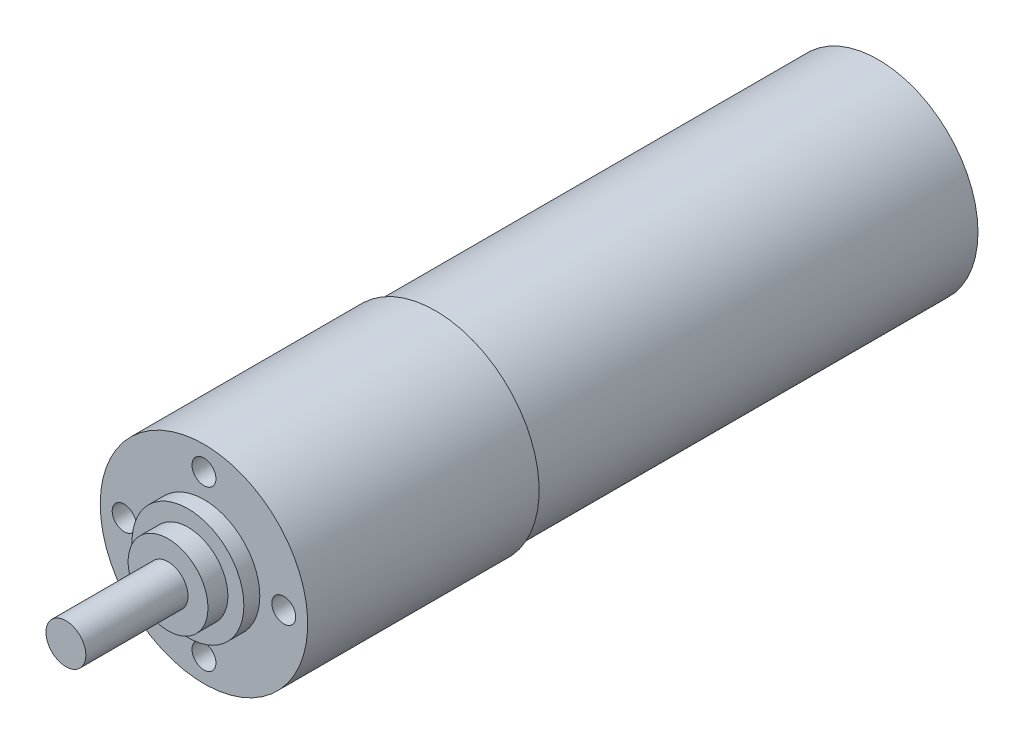
SolidWorks part; units mm, degrees
ref_plane "정면" through (0, 0, 0) normal (0, 0, 1) x (1, 0, 0)
ref_plane "윗면" through (0, 0, 0) normal (0, 1, 0) x (1, 0, 0)
ref_plane "우측면" through (0, 0, 0) normal (1, 0, 0) x (0, 0, -1)
sketch "스케치1" plane through (0, 0, 0) normal (0, 0, 1) x (1, 0, 0)
  circle A0 centre (0, 0) radius 12.5
  dimension "D1" = 25
extrude "돌출1" add sketch "스케치1" along normal blind 55.5
sketch "스케치2" plane through (0, 0, 55.5) normal (0, 0, 1) x (1, 0, 0)
  circle A0 centre (0, 0) radius 13
extrude "보스-돌출1" add sketch "스케치2" along normal blind 29
sketch "스케치3" plane through (0, 0, 84.5) normal (0, 0, 1) x (1, 0, 0)
  circle A0 centre (0, 0) radius 7
extrude "보스-돌출2" add sketch "스케치3" along normal blind 2
sketch "스케치4" plane through (0, 0, 86.5) normal (0, 0, 1) x (1, 0, 0)
  circle A0 centre (0, 0) radius 5
extrude "보스-돌출3" add sketch "스케치4" along normal blind 2.5
sketch "스케치5" plane through (0, 0, 89) normal (0, 0, 1) x (1, 0, 0)
  circle A0 centre (0, 0) radius 2.5
extrude "보스-돌출4" add sketch "스케치5" along normal blind 12.8
sketch "스케치6" plane through (0, 0, 84.5) normal (0, 0, 1) x (1, 0, 0)
  circle A0 centre (0, 0) radius 10 construction
  circle A1 centre (0, 10) radius 1.5
  circle A2 centre (10, 0) radius 1.5
  circle A3 centre (0, -10) radius 1.5
  circle A4 centre (-10, 0) radius 1.5
  point P14 (0, 0)
  dimension "D1" = 4
extrude "컷-돌출1" cut sketch "스케치6" against normal blind 4
